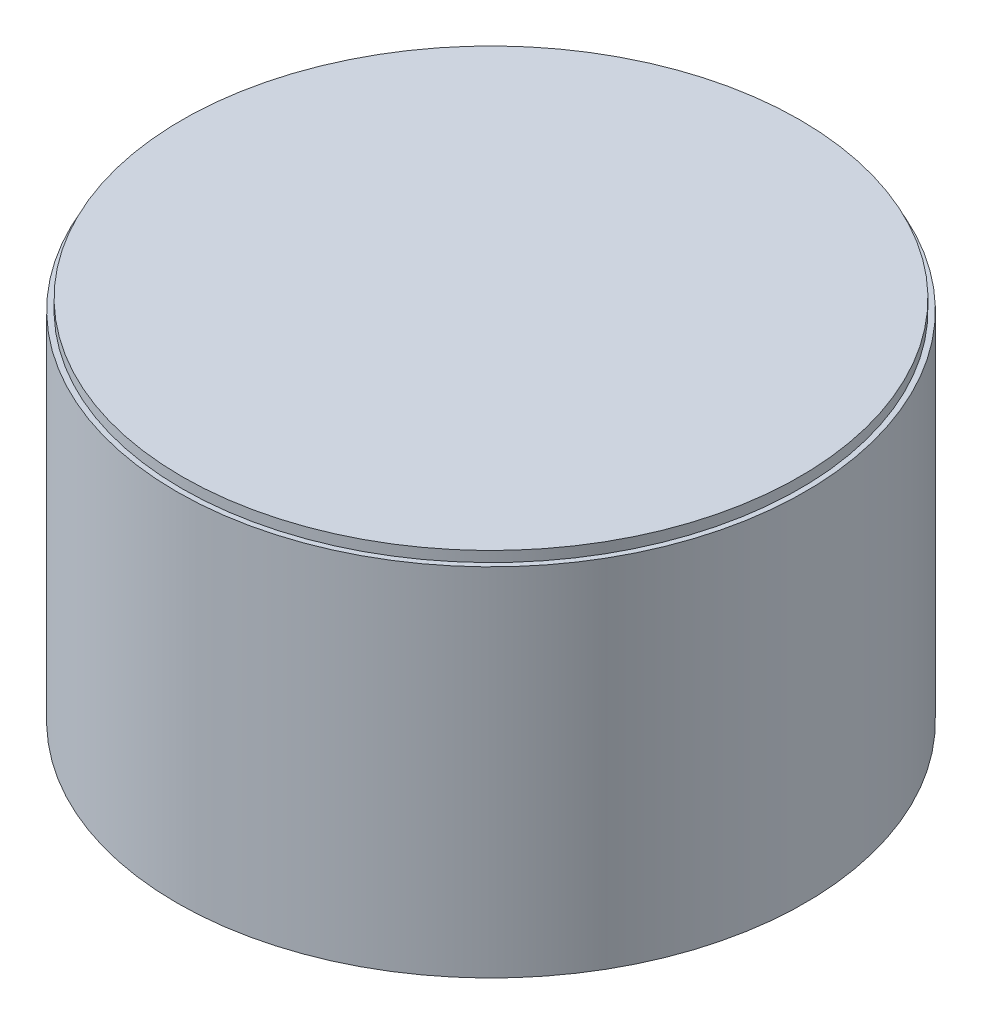
SolidWorks part; units mm, degrees
ref_plane "Front Plane" through (0, 0, 0) normal (0, 0, 1) x (1, 0, 0)
ref_plane "Top Plane" through (0, 0, 0) normal (0, 1, 0) x (1, 0, 0)
ref_plane "Right Plane" through (0, 0, 0) normal (1, 0, 0) x (0, 0, -1)
sketch "Sketch1" plane through (0, 0, 0) normal (0, 1, 0) x (1, 0, 0)
  circle A0 centre (0, 0) radius 3
  dimension "D1" = 6
extrude "Boss-Extrude1" add sketch "Sketch1" along normal mid plane 3.4
sketch "Sketch2" plane through (0, 1.7, 0) normal (0, 1, 0) x (1, 0, 0)
  circle A0 centre (0, 0) radius 2.95
  dimension "D1" = 5.9
extrude "Boss-Extrude2" add sketch "Sketch2" along normal blind 0.1
